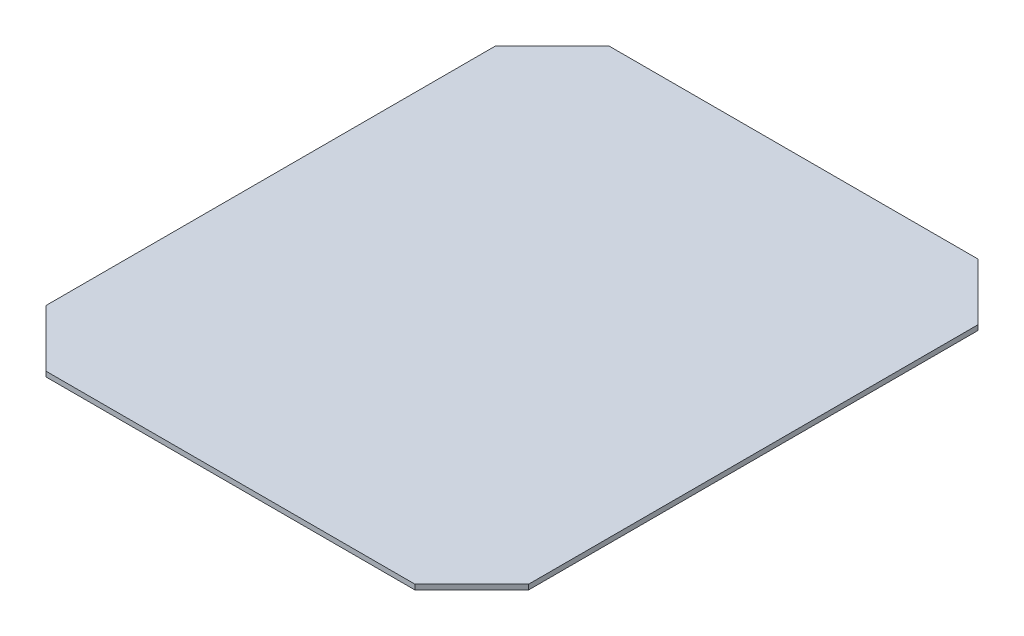
SolidWorks part; units mm, degrees
ref_plane "Front Plane" through (0, 0, 0) normal (0, 0, 1) x (1, 0, 0)
ref_plane "Top Plane" through (0, 0, 0) normal (0, 1, 0) x (1, 0, 0)
ref_plane "Right Plane" through (0, 0, 0) normal (1, 0, 0) x (0, 0, -1)
sketch "Sketch1" plane through (0, 0, 0) normal (0, 1, 0) x (1, 0, 0)
  line L0 (-61.766, 66.5353) -> (-25.845, 102.4564)
  line L1 (-61.766, 102.4564) -> (243.034, 102.4564)
  line L2 (-61.766, 102.4564) -> (-61.766, -253.1436)
  line L3 (-61.766, -253.1436) -> (243.034, -253.1436)
  line L4 (243.034, 102.4564) -> (243.034, -253.1436)
  line L5 (90.634, 95.069) -> (90.634, -294.9418) construction
  line L6 (-86.5248, -75.3436) -> (277.558, -75.3436) construction
  line L7 (243.034, 66.5353) -> (207.1129, 102.4564)
  line L8 (243.034, -217.2226) -> (207.1129, -253.1436)
  line L9 (-61.766, -217.2226) -> (-25.845, -253.1436)
  point P8 (90.634, 102.4564)
  point P11 (-61.766, -75.3436)
  dimension "D1" = 304.8
  dimension "D2" = 355.6
  dimension "D3" = 45
  dimension "D4" = 50.8
extrude "Boss-Extrude1" add sketch "Sketch1" along normal blind 3.175
